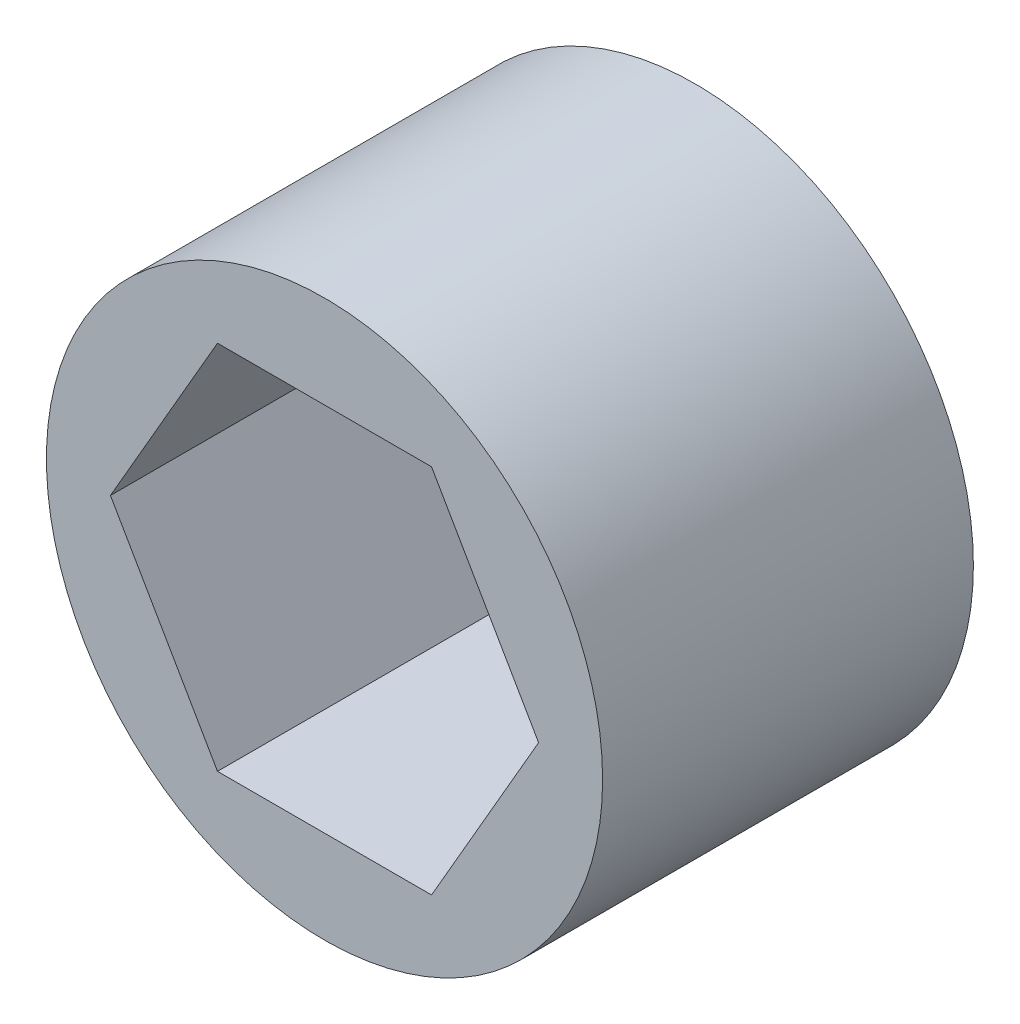
SolidWorks part; units mm, degrees
material "Nylon 101"
ref_plane "Front Plane" through (0, 0, 0) normal (0, 0, 1) x (1, 0, 0)
ref_plane "Top Plane" through (0, 0, 0) normal (0, 1, 0) x (1, 0, 0)
ref_plane "Right Plane" through (0, 0, 0) normal (1, 0, 0) x (0, 0, -1)
sketch "Sketch1" plane through (0, 0, 0) normal (0, 0, 1) x (1, 0, 0)
  line L1 (3.6662, 6.35) -> (-3.6662, 6.35)
  line L2 (-3.6662, 6.35) -> (-7.3323, 0)
  line L3 (-7.3323, 0) -> (-3.6662, -6.35)
  line L4 (-3.6662, -6.35) -> (3.6662, -6.35)
  line L5 (3.6662, -6.35) -> (7.3323, 0)
  line L6 (7.3323, 0) -> (3.6662, 6.35)
  circle A0 centre (0, 0) radius 9.525
  circle A1 centre (0, 0) radius 6.35 construction
  point P3 (0, 6.35)
  dimension "D2" = 19.05
  dimension "D1" = 12.7
extrude "Boss-Extrude1" add sketch "Sketch1" along normal blind 12.7
